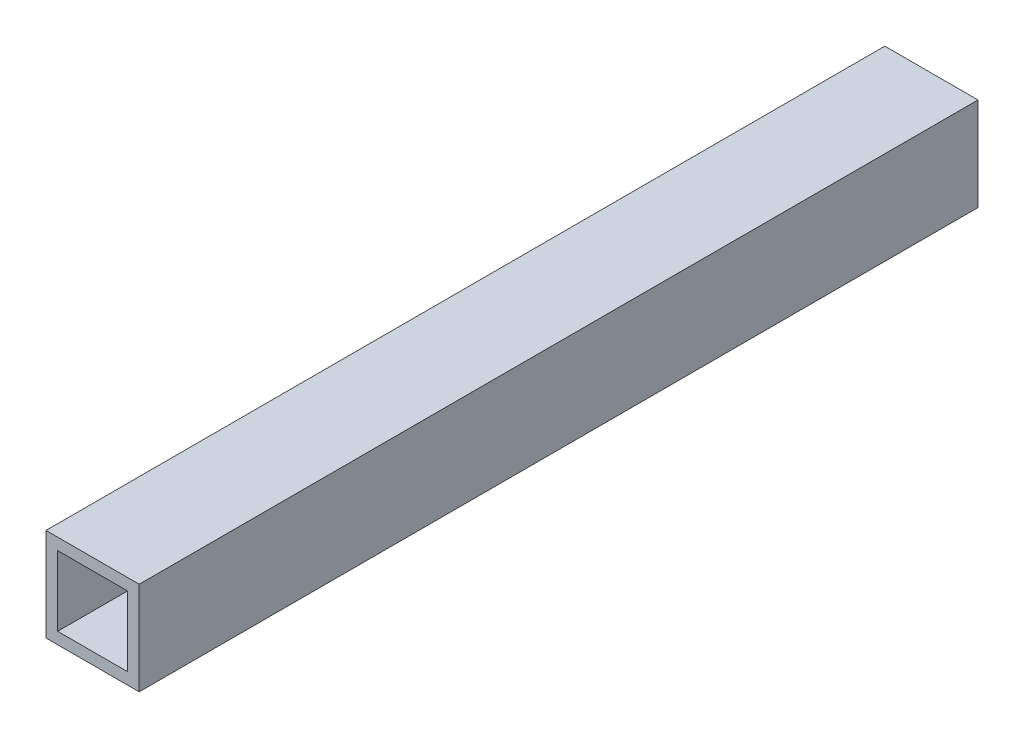
SolidWorks part; units mm, degrees
ref_plane "Front Plane" through (0, 0, 0) normal (0, 0, 1) x (1, 0, 0)
ref_plane "Top Plane" through (0, 0, 0) normal (0, 1, 0) x (1, 0, 0)
ref_plane "Right Plane" through (0, 0, 0) normal (1, 0, 0) x (0, 0, -1)
sketch "Sketch1" plane through (0, 0, 0) normal (0, 0, 1) x (1, 0, 0)
  line L1 (-12.7, -12.7) -> (12.7, -12.7)
  line L2 (-12.7, -12.7) -> (-12.7, 12.7)
  line L3 (-12.7, 12.7) -> (12.7, 12.7)
  line L4 (12.7, -12.7) -> (12.7, 12.7)
  line L5 (-12.7, -12.7) -> (12.7, 12.7) construction
  line L6 (-12.7, 12.7) -> (12.7, -12.7) construction
  point P0 (0, 0)
  dimension "D1" = 25.4
  dimension "D2" = 25.4
extrude "Boss-Extrude1" add sketch "Sketch1" along normal mid plane 228.6
shell "Shell1" thickness 3.175
